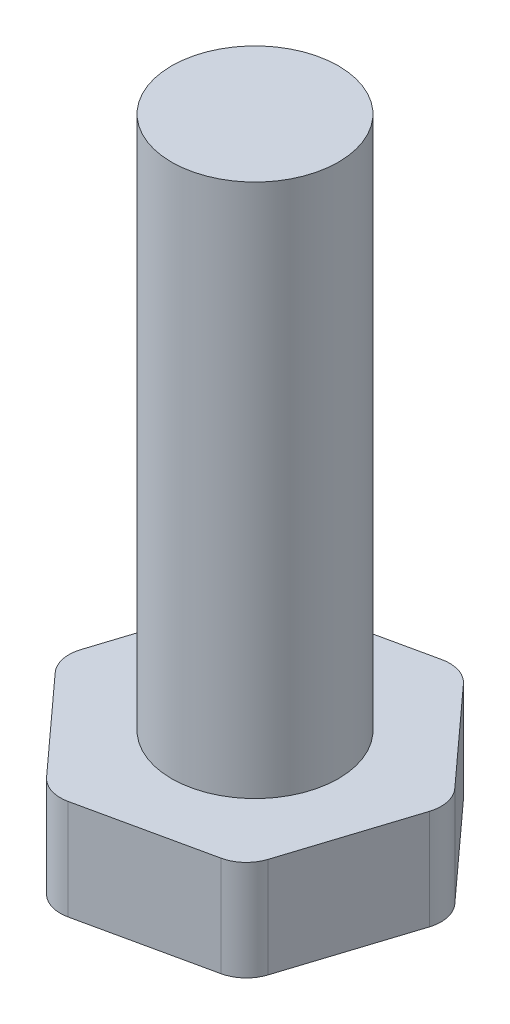
SolidWorks part; units mm, degrees
material "1.4006 (X10Cr13)"
ref_plane "前视" through (0, 0, 0) normal (0, 0, 1) x (1, 0, 0)
ref_plane "上视" through (0, 0, 0) normal (0, 1, 0) x (1, 0, 0)
ref_plane "右视" through (0, 0, 0) normal (1, 0, 0) x (0, 0, -1)
sketch "草图2" plane through (0, 0, 0) normal (0, 1, 0) x (1, 0, 0)
  line L1 (7.3249, 4.1712) -> (8.8473, 8.9339)
  line L2 (8.8473, 8.9339) -> (5.4839, 12.6336)
  line L3 (5.4839, 12.6336) -> (0.5982, 11.5706)
  line L4 (0.5982, 11.5706) -> (-0.9241, 6.808)
  line L5 (-0.9241, 6.808) -> (2.4392, 3.1083)
  line L6 (2.4392, 3.1083) -> (7.3249, 4.1712)
  circle A0 centre (3.9616, 7.8709) radius 4.3301 construction
  dimension "D1" = 5
extrude "凸台-拉伸1" add sketch "草图2" along normal blind 3 contours L3 L4 L5 L6 L1 L2
sketch "草图4" plane through (0, 3, 0) normal (0, 1, 0) x (1, 0, 0)
  line L0 (0.5982, 11.5706) -> (7.3249, 4.1712) construction
  line L1 (5.4839, 12.6336) -> (2.4392, 3.1083) construction
  circle A0 centre (3.9616, 7.8709) radius 2.5
  dimension "D1" = 5
extrude "凸台-拉伸2" add sketch "草图4" along normal blind 16
fillet "圆角1" radius 1 6 edges at (2.4392, 1.5, -3.1083) (-0.9241, 1.5, -6.808) (7.3249, 1.5, -4.1712) (8.8473, 1.5, -8.9339) (0.5982, 1.5, -11.5706) (5.4839, 1.5, -12.6336)
